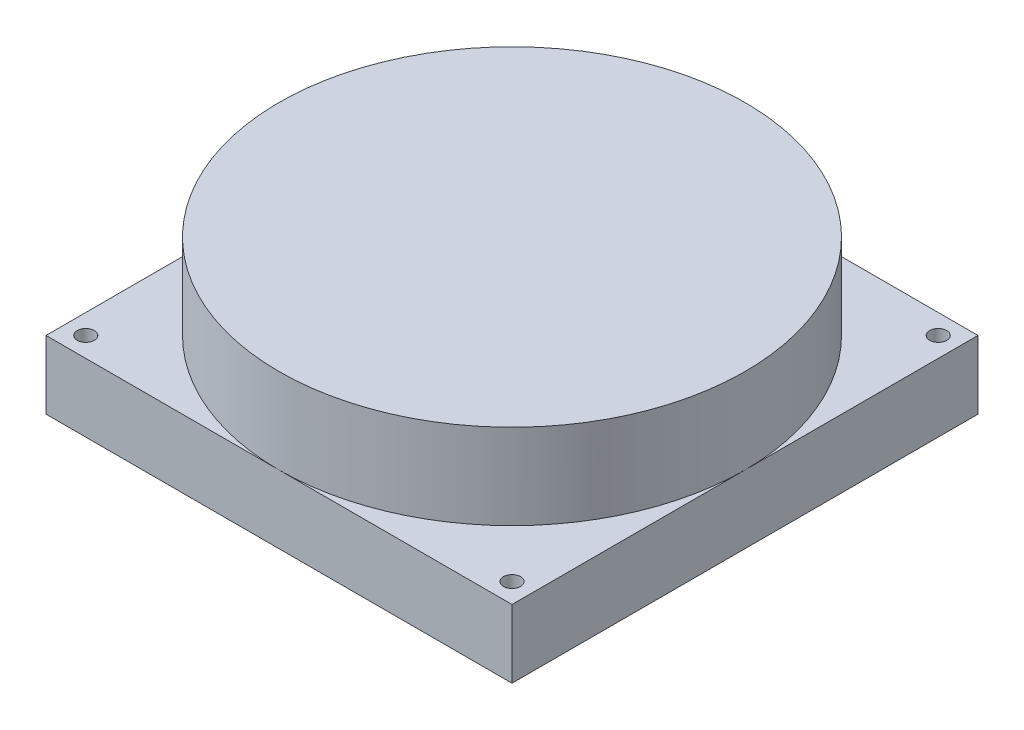
SolidWorks part; units mm, degrees
ref_plane "Front Plane" through (0, 0, 0) normal (0, 0, 1) x (1, 0, 0)
ref_plane "Top Plane" through (0, 0, 0) normal (0, 1, 0) x (1, 0, 0)
ref_plane "Right Plane" through (0, 0, 0) normal (1, 0, 0) x (0, 0, -1)
sketch "Sketch1" plane through (0, 0, 0) normal (0, 1, 0) x (1, 0, 0)
  line L1 (-89.0469, 26.3724) -> (-7.0469, 26.3724)
  line L2 (-89.0469, 26.3724) -> (-89.0469, -55.6276)
  line L3 (-89.0469, -55.6276) -> (-7.0469, -55.6276)
  line L4 (-7.0469, 26.3724) -> (-7.0469, -55.6276)
  dimension "D1" = 82
  dimension "D2" = 82
extrude "Boss-Extrude1" add sketch "Sketch1" along normal blind 12
sketch "Sketch2" plane through (0, 0, 0) normal (0, -1, 0) x (1, 0, 0)
  line L0 (-89.0469, 55.6276) -> (-7.0469, 55.6276) construction
  line L1 (-89.0469, -26.3724) -> (-89.0469, 55.6276) construction
  line L2 (-7.0469, 55.6276) -> (-7.0469, -26.3724) construction
  line L3 (-7.0469, -26.3724) -> (-89.0469, -26.3724) construction
  circle A0 centre (-85.5469, 52.1276) radius 1.5
  circle A1 centre (-10.5469, 52.1276) radius 1.5
  circle A2 centre (-85.5469, -22.8724) radius 1.5
  circle A3 centre (-10.5469, -22.8724) radius 1.5
  dimension "D1" = 3.5
  dimension "D2" = 3.5
  dimension "D3" = 3
  dimension "D4" = 3
  dimension "D6" = 3
  dimension "D7" = 3.5
  dimension "D8" = 3
  dimension "D5" = 3.5
extrude "Cut-Extrude1" cut sketch "Sketch2" against normal through all
sketch "Sketch3" plane through (0, 12, 0) normal (0, 1, 0) x (1, 0, 0)
  line L0 (-7.0469, -55.6276) -> (-7.0469, 26.3724) construction
  line L1 (-89.0469, 26.3724) -> (-89.0469, -55.6276) construction
  line L2 (-89.0469, -55.6276) -> (-7.0469, -55.6276) construction
  circle A0 centre (-48.0469, -14.6276) radius 41
extrude "Boss-Extrude2" add sketch "Sketch3" along normal blind 15
sketch "Sketch4" plane through (0, 0, 0) normal (0, -1, 0) x (1, 0, 0)
  line L0 (-7.0469, -26.3724) -> (-89.0469, -26.3724) construction
  line L1 (-62.0469, 5.6276) -> (-34.0469, 5.6276) construction
  line L2 (-62.0469, 5.6276) -> (-62.0469, 32.6276) construction
  line L3 (-62.0469, 32.6276) -> (-34.0469, 32.6276) construction
  line L4 (-34.0469, 5.6276) -> (-34.0469, 32.6276) construction
  line L5 (-89.0469, 55.6276) -> (-7.0469, 55.6276) construction
  circle A0 centre (-57.0469, 14.8776) radius 1.5
  circle A1 centre (-39.0469, 14.8776) radius 1.5
  point P4 (-48.0469, 5.6276)
  point P7 (-48.0469, -26.3724)
  dimension "D4" = 17.75
  dimension "D5" = 3
  dimension "D6" = 3
  dimension "D7" = 5
  dimension "D8" = 18
  dimension "D1" = 28
  dimension "D2" = 27
  dimension "D3" = 23
extrude "Cut-Extrude2" cut sketch "Sketch4" against normal blind 5
